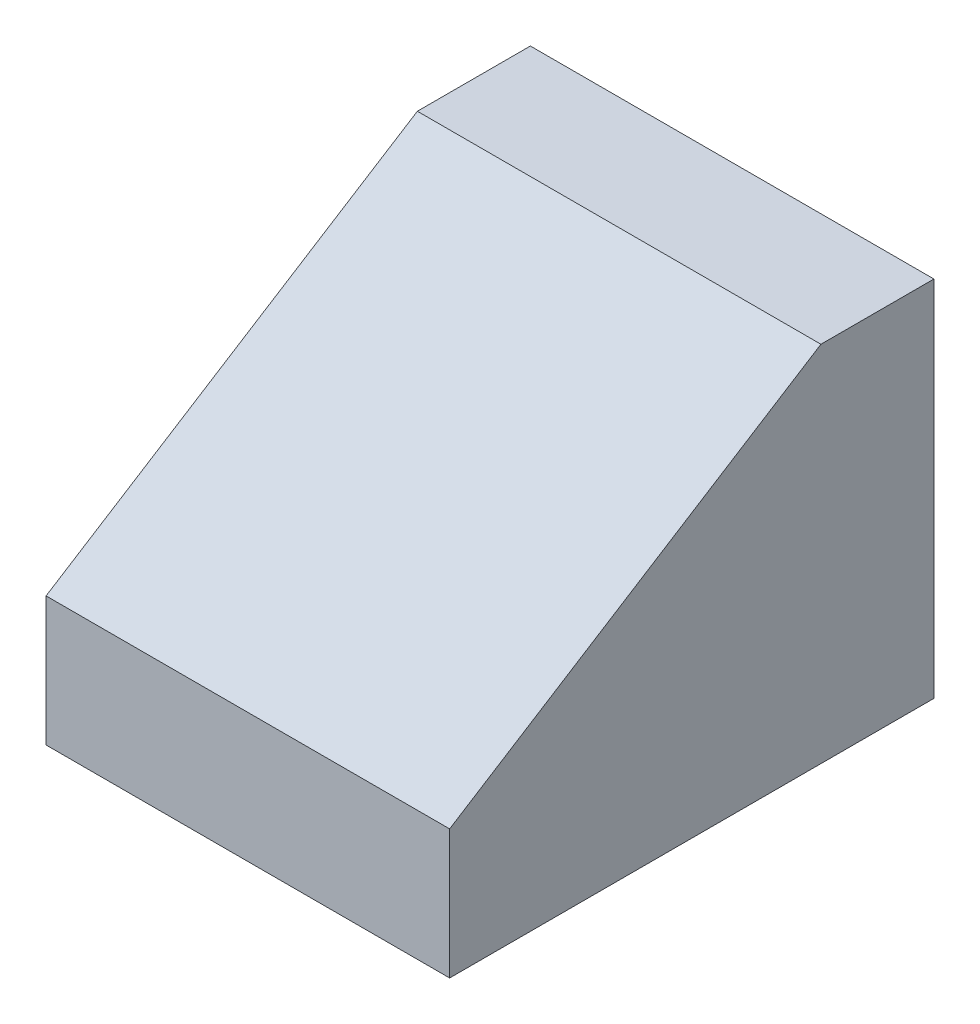
SolidWorks part; units mm, degrees
ref_plane "Plan de face" through (0, 0, 0) normal (0, 0, 1) x (1, 0, 0)
ref_plane "Plan de dessus" through (0, 0, 0) normal (0, 1, 0) x (1, 0, 0)
ref_plane "Plan de droite" through (0, 0, 0) normal (1, 0, 0) x (0, 0, -1)
sketch "Esquisse1" plane through (0, 0, 0) normal (1, 0, 0) x (0, 0, -1)
  line L0 (-49.2537, 0) -> (70.7463, 0)
  line L1 (70.7463, 0) -> (70.7463, 90)
  line L2 (70.7463, 90) -> (42.7463, 90)
  line L3 (42.7463, 90) -> (-49.2537, 32)
  line L4 (-49.2537, 32) -> (-49.2537, 0)
  dimension "D1" = 90
  dimension "D2" = 120
  dimension "D3" = 32
  dimension "D4" = 28
extrude "Boss.-Extru.1" add sketch "Esquisse1" along normal mid plane 100
